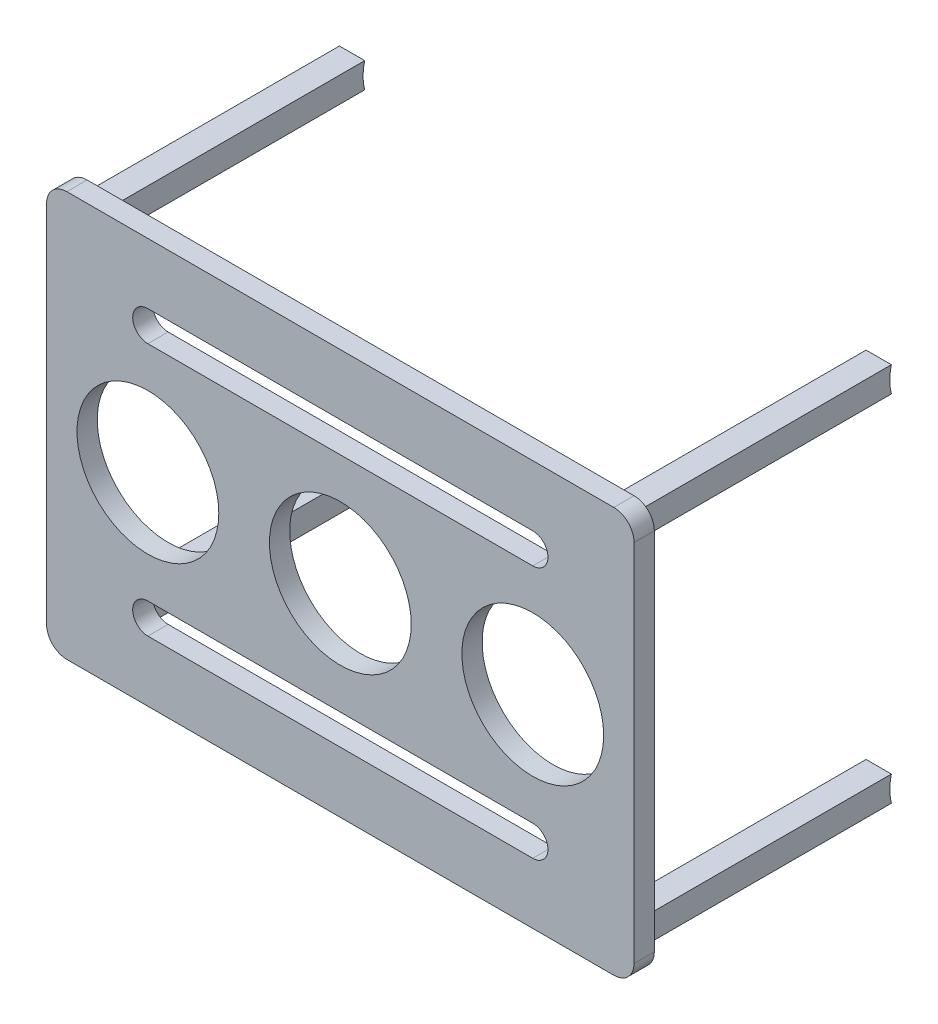
SolidWorks part; units mm, degrees
ref_plane "Front Plane" through (0, 0, 0) normal (0, 0, 1) x (1, 0, 0)
ref_plane "Top Plane" through (0, 0, 0) normal (0, 1, 0) x (1, 0, 0)
ref_plane "Right Plane" through (0, 0, 0) normal (1, 0, 0) x (0, 0, -1)
sketch "Sketch1" plane through (0, 0, 0) normal (0, 0, 1) x (1, 0, 0)
  line L1 (-29, -20) -> (29, -20)
  line L2 (-29, -20) -> (-29, 20)
  line L3 (-29, 20) -> (29, 20)
  line L4 (29, -20) -> (29, 20)
  line L5 (-29, -20) -> (29, 20) construction
  line L6 (-29, 20) -> (29, -20) construction
  point P0 (0, 0)
extrude "Boss-Extrude2" add sketch "Sketch1" along normal blind 2
sketch "Sketch2" plane through (0, 0, 2) normal (0, 0, 1) x (1, 0, 0)
  line L13 (-19, 12.5) -> (19, 12.5) construction
  line L14 (-19, 13.9997) -> (19, 13.9997)
  line L15 (-19, 11.0003) -> (19, 11.0003)
  line L16 (-19, -12.5) -> (19, -12.5) construction
  line L17 (-19, -11) -> (19, -11)
  line L18 (-19, -14) -> (19, -14)
  circle A0 centre (0, 0) radius 7
  circle A1 centre (19, 0) radius 7
  circle A2 centre (-19, 0) radius 7
  arc A3 (-19, 13.9997) -> (-19, 11.0003) centre (-19, 12.5) ccw
  arc A4 (19, 11.0003) -> (19, 13.9997) centre (19, 12.5) ccw
  arc A5 (-19, -11) -> (-19, -14) centre (-19, -12.5) ccw
  arc A6 (19, -14) -> (19, -11) centre (19, -12.5) ccw
  point P23 (0, 12.5)
  point P28 (0, -12.5)
extrude "Cut-Extrude1" cut sketch "Sketch2" against normal blind 2
fillet "Fillet1" radius 2 4 edges at (-29, 20, 1) (-29, -20, 1) (29, -20, 1) (29, 20, 1)
sketch "Sketch4" plane through (0, 0, 0) normal (0, 0, -1) x (-1, 0, 0)
  circle A0 centre (25.5, 12.5) radius 2.5
  circle A1 centre (25.5, -12.5) radius 2.5
  circle A2 centre (-25.5, -12.5) radius 2.5
  circle A3 centre (-25.5, 12.5) radius 2.5
extrude "Cut-Extrude5" cut sketch "Sketch4" against normal blind 2
sketch "Sketch6" plane through (0, 0, 0) normal (0, 0, -1) x (-1, 0, 0)
  circle A0 centre (25.5, 12.5) radius 2.5
  circle A1 centre (25.5, -12.5) radius 2.5
  circle A2 centre (-25.5, -12.5) radius 2.5
  circle A3 centre (-25.5, 12.5) radius 2.5
extrude "Boss-Extrude3" add sketch "Sketch6" against normal up to surface (2 mm away) up to face at (28, 12.5, 2)
sketch "Sketch7" plane through (0, 0, 0) normal (0, 0, -1) x (-1, 0, 0)
  line L0 (0, 0) -> (26, 0)
  line L1 (26, 0) -> (26, -17.5)
  line L2 (26, -17.5) -> (26, 17.5)
  line L3 (0, 0) -> (-26, 0)
  line L4 (-26, 0) -> (-26, 17.5)
  line L5 (-26, 17.5) -> (-26, -17.5)
  line L6 (-27.25, -16.25) -> (-24.75, -18.75) construction
  line L7 (-27.25, 18.75) -> (-24.75, 18.75)
  line L8 (-27.25, 18.75) -> (-27.25, 16.25)
  line L9 (-27.25, 16.25) -> (-24.75, 16.25)
  line L10 (-24.75, 18.75) -> (-24.75, 16.25)
  line L11 (-27.25, 18.75) -> (-24.75, 16.25) construction
  line L12 (-27.25, 16.25) -> (-24.75, 18.75) construction
  line L13 (-27.25, -18.75) -> (-24.75, -16.25) construction
  line L14 (-24.75, -18.75) -> (-24.75, -16.25)
  line L15 (-27.25, -16.25) -> (-24.75, -16.25)
  line L16 (-27.25, -18.75) -> (-27.25, -16.25)
  line L17 (-27.25, -18.75) -> (-24.75, -18.75)
  line L18 (0, 0) -> (0, 20)
  line L19 (-27, 20) -> (27, 20) construction
  line L20 (27.25, -18.75) -> (27.25, -16.25)
  line L21 (27.25, -18.75) -> (24.75, -18.75)
  line L22 (24.75, -18.75) -> (24.75, -16.25)
  line L23 (27.25, -16.25) -> (24.75, -16.25)
  line L24 (27.25, 16.25) -> (24.75, 16.25)
  line L25 (27.25, 16.25) -> (24.75, 18.75) construction
  line L26 (27.25, 18.75) -> (24.75, 16.25) construction
  line L27 (24.75, 18.75) -> (24.75, 16.25)
  line L28 (27.25, 18.75) -> (27.25, 16.25)
  line L29 (27.25, 18.75) -> (24.75, 18.75)
  circle A0 centre (19, 0) radius 7 construction
  circle A1 centre (-19, 0) radius 7 construction
extrude "Boss-Extrude5" add sketch "Sketch7" along normal blind 30
sketch "Sketch8" plane through (-27.25, 0, 0) normal (-1, 0, 0) x (0, 0, 1)
  line L0 (-30, 18.75) -> (-30, 16.25) construction
  line L1 (-30, -18.75) -> (-30, -16.25) construction
  circle A0 centre (-30, 17.5) radius 5
  circle A1 centre (-30, -17.5) radius 5
extrude "Cut-Extrude6" cut sketch "Sketch8" against normal blind 66
